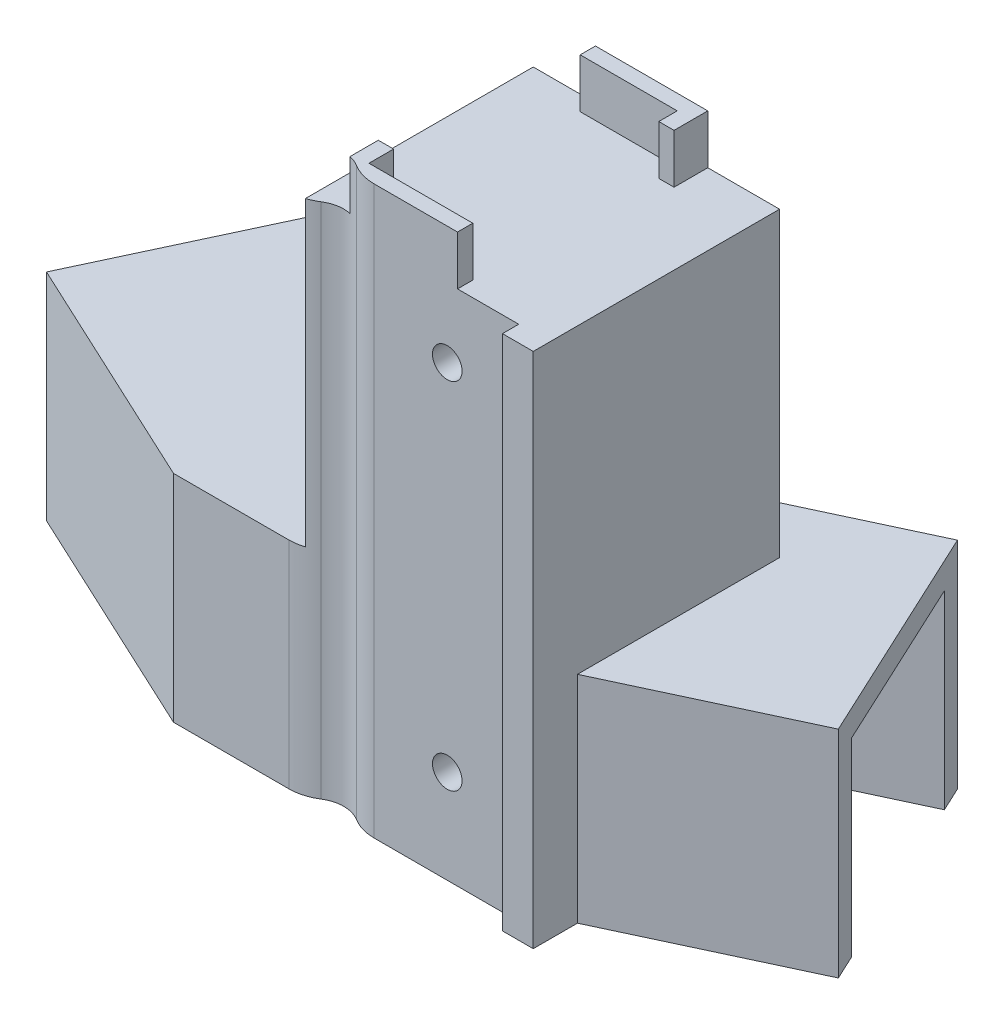
SolidWorks part; units mm, degrees
ref_plane "Front Plane" through (0, 0, 0) normal (0, 0, 1) x (1, 0, 0)
ref_plane "Top Plane" through (0, 0, 0) normal (0, 1, 0) x (1, 0, 0)
ref_plane "Right Plane" through (0, 0, 0) normal (1, 0, 0) x (0, 0, -1)
sketch "Sketch1" plane through (0, 0, 0) normal (0, 1, 0) x (1, 0, 0)
  line L2 (30.0892, 10.7345) -> (40.8237, -12.2857)
  line L3 (40.8237, -12.2857) -> (12.7, -25.4)
  line L8 (12.7, -25.4) -> (0, -25.4)
  line L10 (0, 0) -> (0, -25.4)
  line L11 (0, 0) -> (7.069, 0)
  line L12 (7.069, 0) -> (30.0892, 10.7345)
  point P4 (0, 0)
  dimension "D1" = 25.4
  dimension "D2" = 25.4
  dimension "D3" = 155
  dimension "D4" = 25.4
  dimension "D5" = 12.7
extrude "Boss-Extrude1" add sketch "Sketch1" along normal blind 22.225
sketch "Sketch2" plane through (28.8266, 0, -13.4421) normal (0.9063, 0, -0.4226) x (-0.4226, 0, -0.9063)
  line L0 (-28.3875, 0) -> (-2.9875, 0) construction
  line L1 (-25.5935, 0) -> (-5.7815, 0)
  line L2 (-25.5935, 0) -> (-25.5935, 19.558)
  line L3 (-25.5935, 19.558) -> (-5.7815, 19.558)
  line L4 (-5.7815, 0) -> (-5.7815, 19.558)
  line L6 (-28.3875, 22.225) -> (-2.9875, 22.225) construction
  point P8 (-15.6875, 19.558)
  point P11 (-15.6875, 22.225)
  dimension "D1" = 19.812
  dimension "D2" = 19.558
extrude "Cut-Extrude1" cut sketch "Sketch2" against normal blind 25.4
mirror "Mirror1" about plane through (0, 22.225, 0) normal (1, 0, 0) of "Cut-Extrude1", "Boss-Extrude1"
sketch "Sketch4" plane through (0, 22.225, 0) normal (0, 1, 0) x (1, 0, 0)
  line L0 (12.7, -25.4) -> (22.479, -25.4)
  line L1 (22.479, -25.4) -> (22.479, -20.84)
  line L2 (19.05, -23.9776) -> (19.05, -25.4) construction
  line L8 (7.069, 0) -> (-7.069, 0)
  line L9 (-7.069, 0) -> (-30.0892, 10.7345)
  line L10 (-30.0892, 10.7345) -> (-40.8237, -12.2857)
  line L11 (-40.8237, -12.2857) -> (-12.7, -25.4)
  line L12 (-12.7, -25.4) -> (12.7, -25.4)
  line L13 (12.7, -25.4) -> (40.8237, -12.2857)
  line L14 (40.8237, -12.2857) -> (30.0892, 10.7345)
  line L15 (30.0892, 10.7345) -> (7.069, 0)
  line L16 (7.069, 0) -> (-7.069, 0)
  line L17 (-7.069, 0) -> (-30.0892, 10.7345)
  line L18 (-30.0892, 10.7345) -> (-40.8237, -12.2857)
  line L19 (-40.8237, -12.2857) -> (-12.7, -25.4)
  line L20 (-12.7, -25.4) -> (12.7, -25.4)
  line L21 (12.7, -25.4) -> (40.8237, -12.2857)
  line L22 (40.8237, -12.2857) -> (30.0892, 10.7345)
  line L23 (30.0892, 10.7345) -> (7.069, 0)
  line M15 (12.7, -25.4) -> (40.8237, -12.2857)
  dimension "D2" = 3.429
  dimension "D1" = 0
extrude "Boss-Extrude3" add sketch "Sketch4" against normal up to surface (22.225 mm away) contours L0 L1 M15 up to face at (0, 0, 6.4403)
sketch "Sketch6" plane through (0, 0, 0) normal (0, -1, 0) x (1, 0, 0)
  line L0 (19.05, 23.9776) -> (19.05, 25.4) construction
  line L1 (19.05, 23.9776) -> (4.3994, 23.9776) construction
  line L2 (19.05, 23.9776) -> (19.05, 25.4) construction
  line L3 (19.05, 23.9776) -> (4.3994, 23.9776) construction
  line L4 (-12.7, 25.4) -> (22.479, 25.4) construction
  line L5 (-3.1381, 25.4) -> (19.05, 25.4) construction
  line L6 (19.304, 23.7236) -> (4.3994, 23.7236)
  line L8 (19.304, 23.7236) -> (19.304, 25.4)
  line L9 (-3.4214, 25.654) -> (19.304, 25.654) construction
  line L10 (-3.3949, 25.4) -> (19.304, 25.4)
  line L11 (19.304, 23.7236) -> (19.304, 25.654) construction
  arc A0 (3.1381, 25.4) -> (1.6921, 23.1961) centre (0, 25.8826) ccw construction
  arc A1 (4.3994, 23.9776) -> (1.6921, 23.1961) centre (4.3994, 18.8976) ccw construction
  arc A2 (-3.1381, 25.4) -> (1.6921, 23.1961) centre (0, 25.8826) ccw construction
  arc A3 (4.3994, 23.9776) -> (1.6921, 23.1961) centre (4.3994, 18.8976) ccw construction
  arc A4 (4.3994, 23.7236) -> (1.8274, 22.9811) centre (4.3994, 18.8976) ccw
  arc A5 (-3.3949, 25.4) -> (1.8274, 22.9811) centre (0, 25.8826) ccw
  arc A6 (-3.4214, 25.654) -> (1.8274, 22.9811) centre (0, 25.8826) ccw construction
  dimension "D1" = 0.254
extrude "Cut-Extrude2" cut sketch "Sketch6" against normal through all
sketch "Sketch11" plane through (0, 22.225, 0) normal (0, 1, 0) x (1, 0, 0)
  line L0 (22.479, -20.84) -> (22.479, 0)
  line L1 (22.479, 0) -> (-2.921, 0)
  line L2 (-2.921, 0) -> (-2.921, -24.0865)
  line L12 (4.3994, -23.7236) -> (19.304, -23.7236)
  line L13 (19.304, -23.7236) -> (19.304, -25.4)
  line L14 (19.304, -25.4) -> (22.479, -25.4)
  line L15 (22.479, -25.4) -> (22.479, -20.84)
  line L16 (22.479, -20.84) -> (40.8237, -12.2857)
  line L17 (40.8237, -12.2857) -> (30.0892, 10.7345)
  line L18 (30.0892, 10.7345) -> (7.069, 0)
  line L19 (7.069, 0) -> (-7.069, 0)
  line L20 (-7.069, 0) -> (-30.0892, 10.7345)
  line L21 (-30.0892, 10.7345) -> (-40.8237, -12.2857)
  line L22 (-40.8237, -12.2857) -> (-12.7, -25.4)
  line L23 (-12.7, -25.4) -> (-3.3949, -25.4)
  line L24 (4.3994, -23.7236) -> (19.304, -23.7236)
  line L25 (19.304, -23.7236) -> (19.304, -25.4)
  line L26 (19.304, -25.4) -> (22.479, -25.4)
  line L27 (22.479, -25.4) -> (22.479, -20.84)
  line L28 (22.479, -20.84) -> (40.8237, -12.2857)
  line L29 (40.8237, -12.2857) -> (30.0892, 10.7345)
  line L30 (30.0892, 10.7345) -> (7.069, 0)
  line L31 (7.069, 0) -> (-7.069, 0)
  line L32 (-7.069, 0) -> (-30.0892, 10.7345)
  line L33 (-30.0892, 10.7345) -> (-40.8237, -12.2857)
  line L34 (-40.8237, -12.2857) -> (-12.7, -25.4)
  line L35 (-12.7, -25.4) -> (-3.3949, -25.4)
  arc A2 (1.8274, -22.9811) -> (-3.3949, -25.4) centre (0, -25.8826) ccw
  arc A3 (1.8274, -22.9811) -> (4.3994, -23.7236) centre (4.3994, -18.8976) ccw
  arc A4 (1.8274, -22.9811) -> (-3.3949, -25.4) centre (0, -25.8826) ccw
  arc A5 (1.8274, -22.9811) -> (4.3994, -23.7236) centre (4.3994, -18.8976) ccw
  dimension "D3" = 25.4
  dimension "D1" = 0
extrude "Boss-Extrude4" add sketch "Sketch11" along normal up to surface (31.115 mm away)
hole_wizard "#6 Clearance Hole1" positions "Sketch9" profile "Sketch10" hole size "#6" standard "ANSI Inch"
sketch "Sketch9" plane through (0, 0, 23.7236) normal (0, 0, 1) x (1, 0, 0)
  circle A0 centre (11.938, 9.652) radius 2.8 construction
  circle A1 centre (11.938, 46.228) radius 2.8 construction
  point P0 (11.938, 9.652)
  point P6 (11.938, 46.228)
sketch "Sketch10" plane through (11.938, 9.652, 23.7236) normal (1, 0, 0) x (0, -1, 0)
  line L0 (0, 0) -> (0, 13.2819)
  line L1 (0, 13.2819) -> (1.524, 13.2819)
  line L2 (1.524, 13.2819) -> (1.524, 0)
  line L5 (1.524, 0) -> (0, 0)
  line L11 (0, -6.35) -> (0, 107.95) construction
  dimension "Thru Hole Dia." = 3.048
  dimension "Thru Hole Depth" = 13.2819
mirror "Mirror2" about plane through (0, 0, 0) normal (1, 0, 0) of "Cut-Extrude2"
sketch "Sketch13" plane through (0, 53.34, 0) normal (0, 1, 0) x (1, 0, 0)
  line L0 (-2.921, 0) -> (22.479, 0) construction
  line L1 (3.494, 0) -> (15.0768, 0)
  line L2 (3.494, 0) -> (3.494, -1.5748)
  line L3 (3.494, -1.5748) -> (15.0768, -1.5748)
  line L4 (15.0768, 0) -> (15.0768, -1.5748)
  line L5 (19.304, -23.7236) -> (4.3994, -23.7236) construction
  line L11 (19.304, -23.7236) -> (4.3994, -23.7236)
  line L12 (15.0768, -1.5748) -> (13.502, -1.5748)
  line L13 (15.0768, -1.5748) -> (15.0768, -3.4798)
  line L14 (15.0768, -3.4798) -> (13.502, -3.4798)
  line L15 (13.502, -1.5748) -> (13.502, -3.4798)
  line L16 (12.994, -23.7236) -> (12.994, -22.1488)
  line L17 (12.994, -22.1488) -> (2.286, -22.1488)
  line L18 (2.286, -22.1488) -> (2.286, -19.6088)
  line L19 (2.286, -19.6088) -> (0.7112, -19.6088)
  line L20 (0.7112, -19.6088) -> (0.7112, -22.5282)
  line L25 (12.994, -4.9258) -> (12.994, -2.4758) construction
  line L26 (2.794, -12.8793) -> (2.794, -20.7758) construction
  line L27 (12.994, -21.2758) -> (12.994, -18.9258) construction
  line L28 (3.494, -2.9758) -> (3.494, -11.9722) construction
  arc A0 (1.8274, -22.9811) -> (-1.8274, -22.9811) centre (0, -25.8826) ccw construction
  arc A1 (1.8274, -22.9811) -> (4.3994, -23.7236) centre (4.3994, -18.8976) ccw construction
  arc A2 (1.8274, -22.9811) -> (0.7112, -22.5282) centre (0, -25.8826) ccw
  arc A3 (1.8274, -22.9811) -> (4.3994, -23.7236) centre (4.3994, -18.8976) ccw
  arc M8 (-1.8274, -22.9811) -> (1.8274, -22.9811) centre (0, -25.8826) cw
  arc M9 (1.8274, -22.9811) -> (4.3994, -23.7236) centre (4.3994, -18.8976) ccw
  line M10 (4.3994, -23.7236) -> (19.304, -23.7236)
  line M14 (22.479, 0) -> (-2.921, 0)
  dimension "D1" = 20.574
  dimension "D2" = 2.54
  dimension "D3" = 0.508
  dimension "D4" = 1.905
  dimension "D6" = 0.508
extrude "Boss-Extrude5" add sketch "Sketch13" along normal blind 5.08 contours L19 L20 L16 L17 L18 M8 M9 M10 | L4 L2 L3 M14 | L3 L15 L14 L13
equation "\"TOL\"= .01"
equation "\"D1@Sketch2\"=.76 + 2*\"TOL\""
equation "\"D1@Sketch6\"=\"TOL\""
equation "\"D2@Sketch2\"=.76+\"TOL\""
